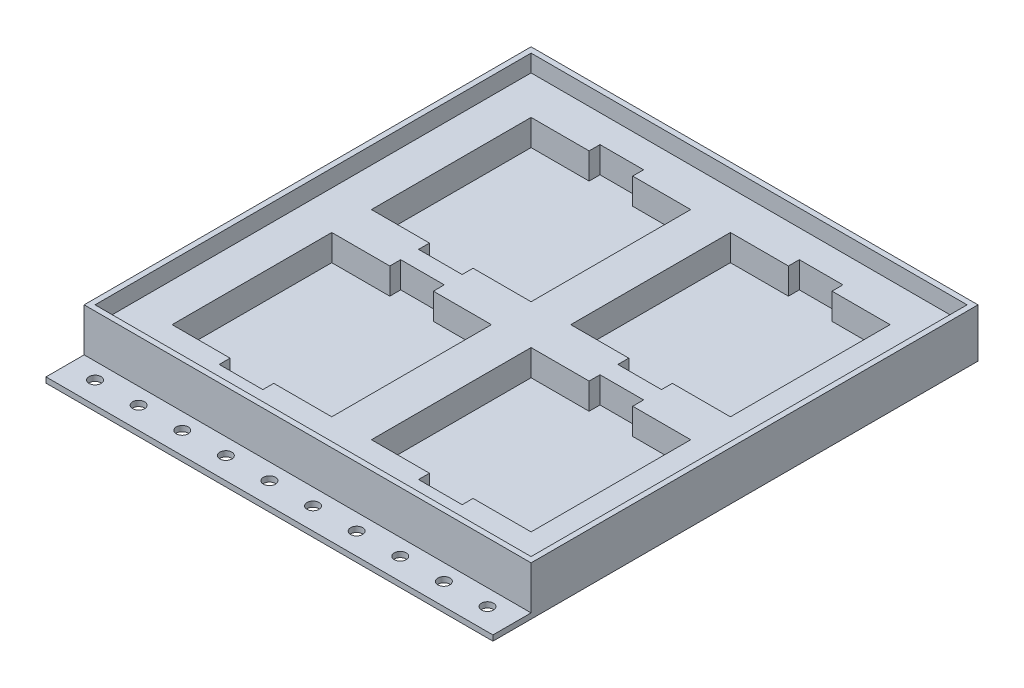
SolidWorks part; units mm, degrees
ref_plane "Front Plane" through (0, 0, 0) normal (0, 0, 1) x (1, 0, 0)
ref_plane "Top Plane" through (0, 0, 0) normal (0, 1, 0) x (1, 0, 0)
ref_plane "Right Plane" through (0, 0, 0) normal (1, 0, 0) x (0, 0, -1)
sketch "Sketch1" plane through (0, 0, 0) normal (0, 1, 0) x (1, 0, 0)
  line L1 (-152.4, -152.4) -> (152.4, -152.4)
  line L2 (-152.4, -152.4) -> (-152.4, 152.4)
  line L3 (-152.4, 152.4) -> (152.4, 152.4)
  line L4 (152.4, -152.4) -> (152.4, 152.4)
  line L5 (104.557, 11.557) -> (11.557, 11.557)
  line L6 (104.557, 11.557) -> (104.557, 104.557)
  line L7 (-11.557, 104.557) -> (-104.557, 104.557)
  line L8 (-11.557, 104.557) -> (-11.557, 11.557)
  line L9 (-11.557, 11.557) -> (-104.557, 11.557)
  line L10 (-104.557, 104.557) -> (-104.557, 11.557)
  line L11 (-11.557, 104.557) -> (-104.557, 11.557) construction
  line L12 (-11.557, 11.557) -> (-104.557, 104.557) construction
  line L13 (104.557, 104.557) -> (11.557, 104.557)
  line L14 (11.557, 11.557) -> (11.557, 104.557)
  line L15 (104.557, 11.557) -> (11.557, 104.557) construction
  line L16 (104.557, 104.557) -> (11.557, 11.557) construction
  line L17 (-104.557, -11.557) -> (-11.557, -11.557)
  line L18 (-104.557, -11.557) -> (-104.557, -104.557)
  line L19 (-104.557, -104.557) -> (-11.557, -104.557)
  line L20 (-11.557, -11.557) -> (-11.557, -104.557)
  line L21 (-104.557, -11.557) -> (-11.557, -104.557) construction
  line L22 (-104.557, -104.557) -> (-11.557, -11.557) construction
  line L23 (11.557, -11.557) -> (104.557, -11.557)
  line L24 (11.557, -11.557) -> (11.557, -104.557)
  line L25 (11.557, -104.557) -> (104.557, -104.557)
  line L26 (104.557, -11.557) -> (104.557, -104.557)
  line L27 (11.557, -11.557) -> (104.557, -104.557) construction
  line L28 (11.557, -104.557) -> (104.557, -11.557) construction
  point P0 (0, 0)
  point P6 (-58.057, 58.057)
  point P11 (58.057, 58.057)
  point P14 (0, 152.4)
  point P16 (-152.4, 0)
  point P18 (-58.057, -58.057)
  point P23 (58.057, -58.057)
  dimension "D1" = 93
  dimension "D2" = 304.8
  dimension "D3" = 23.114
  dimension "D4" = 23.114
extrude "Boss-Extrude1" add sketch "Sketch1" along normal blind 15.24
sketch "Sketch2" plane through (0, 0, 0) normal (0, -1, 0) x (-1, 0, 0)
  line L1 (152.4, -152.4) -> (-152.4, -152.4)
  line L2 (152.4, -152.4) -> (152.4, 152.4)
  line L3 (152.4, 152.4) -> (-152.4, 152.4)
  line L4 (-152.4, -152.4) -> (-152.4, 152.4)
extrude "Boss-Extrude2" add sketch "Sketch2" along normal blind 3.175
sketch "Sketch3" plane through (0, 15.24, 0) normal (0, 1, 0) x (1, 0, 0)
  line L1 (-152.4, -152.4) -> (152.4, -152.4)
  line L2 (-152.4, -152.4) -> (-152.4, 152.4)
  line L3 (-152.4, 152.4) -> (152.4, 152.4)
  line L4 (152.4, -152.4) -> (152.4, 152.4)
  line L5 (-127, -127) -> (127, -127)
  line L6 (-127, -127) -> (-127, 127)
  line L7 (-127, 127) -> (127, 127)
  line L8 (127, -127) -> (127, 127)
  point P10 (-127, 0)
  point P11 (0, 127)
  dimension "D1" = 254
  dimension "D2" = 254
extrude "Boss-Extrude3" add sketch "Sketch3" along normal blind 10
sketch "Sketch4" plane through (0, 25.24, 0) normal (0, 1, 0) x (1, 0, 0)
  line L0 (127, 127) -> (-127, 127) construction
  line L1 (-130.175, 130.175) -> (130.175, 130.175)
  line L2 (-130.175, 130.175) -> (-130.175, -130.175)
  line L3 (-130.175, -130.175) -> (130.175, -130.175)
  line L4 (130.175, 130.175) -> (130.175, -130.175)
  line L5 (-127, 127) -> (-127, -127) construction
  line L6 (127, -127) -> (127, 127) construction
  line L7 (-127, -127) -> (127, -127) construction
  dimension "D1" = 3.175
  dimension "D2" = 3.175
  dimension "D3" = 3.175
  dimension "D4" = 3.175
extrude "Cut-Extrude1" cut sketch "Sketch4" against normal offset from surface (25.24 mm away) 3.175 flip side to cut up to face at (0, -3.175, 0)
sketch "Sketch5" plane through (0, 0, 0) normal (0, 1, 0) x (1, 0, 0)
  line L0 (152.4, -152.4) -> (-152.4, -152.4) construction
  line L1 (-152.4, -152.4) -> (-152.4, 152.4) construction
  circle A0 centre (-139.7, -139.7) radius 3.4925
  circle A1 centre (-114.3, -139.7) radius 3.4925
  circle A2 centre (-88.9, -139.7) radius 3.4925
  circle A3 centre (-63.5, -139.7) radius 3.4925
  circle A4 centre (-38.1, -139.7) radius 3.4925
  circle A5 centre (-12.7, -139.7) radius 3.4925
  circle A6 centre (12.7, -139.7) radius 3.4925
  circle A7 centre (38.1, -139.7) radius 3.4925
  circle A8 centre (63.5, -139.7) radius 3.4925
  circle A9 centre (88.9, -139.7) radius 3.4925
  circle A10 centre (114.3, -139.7) radius 3.4925
  circle A11 centre (139.7, -139.7) radius 3.4925
  circle A12 centre (-139.7, -114.3) radius 3.4925
  circle A13 centre (-139.7, -88.9) radius 3.4925
  circle A14 centre (-139.7, -63.5) radius 3.4925
  circle A15 centre (-139.7, -38.1) radius 3.4925
  circle A16 centre (-139.7, -12.7) radius 3.4925
  circle A17 centre (-139.7, 12.7) radius 3.4925
  circle A18 centre (-139.7, 38.1) radius 3.4925
  circle A19 centre (-139.7, 63.5) radius 3.4925
  circle A20 centre (-139.7, 88.9) radius 3.4925
  circle A21 centre (-139.7, 114.3) radius 3.4925
  circle A22 centre (-139.7, 139.7) radius 3.4925
  circle A23 centre (-114.3, 139.7) radius 3.4925
  circle A24 centre (-88.9, 139.7) radius 3.4925
  circle A25 centre (-63.5, 139.7) radius 3.4925
  circle A26 centre (-38.1, 139.7) radius 3.4925
  circle A27 centre (-12.7, 139.7) radius 3.4925
  circle A28 centre (12.7, 139.7) radius 3.4925
  circle A29 centre (38.1, 139.7) radius 3.4925
  circle A30 centre (63.5, 139.7) radius 3.4925
  circle A31 centre (88.9, 139.7) radius 3.4925
  circle A32 centre (114.3, 139.7) radius 3.4925
  circle A33 centre (139.7, 139.7) radius 3.4925
  circle A34 centre (139.7, 114.3) radius 3.4925
  circle A35 centre (139.7, 88.9) radius 3.4925
  circle A36 centre (139.7, 63.5) radius 3.4925
  circle A37 centre (139.7, 38.1) radius 3.4925
  circle A38 centre (139.7, 12.7) radius 3.4925
  circle A39 centre (139.7, -12.7) radius 3.4925
  circle A40 centre (139.7, -38.1) radius 3.4925
  circle A41 centre (139.7, -63.5) radius 3.4925
  circle A42 centre (139.7, -88.9) radius 3.4925
  circle A43 centre (139.7, -114.3) radius 3.4925
  dimension "D1" = 6.985
  dimension "D2" = 12.7
  dimension "D3" = 12.7
  dimension "D4" = 12
  dimension "D5" = 12
  dimension "D6" = 12
  dimension "D7" = 11
extrude "Cut-Extrude2" cut sketch "Sketch5" against normal through all
sketch "Sketch6" plane through (0, 15.24, 0) normal (0, 1, 0) x (1, 0, 0)
  line L0 (-11.557, 104.557) -> (-104.557, 104.557) construction
  line L1 (-70.757, 104.557) -> (-45.357, 104.557)
  line L2 (-70.757, 104.557) -> (-70.757, 110.907)
  line L3 (-70.757, 110.907) -> (-45.357, 110.907)
  line L4 (-45.357, 104.557) -> (-45.357, 110.907)
  line L5 (11.557, -104.557) -> (104.557, -104.557) construction
  line L6 (-11.557, -11.557) -> (-104.557, -11.557) construction
  line L7 (-70.757, -11.557) -> (-45.357, -11.557)
  line L8 (-70.757, -11.557) -> (-70.757, -5.207)
  line L9 (-70.757, -5.207) -> (-45.357, -5.207)
  line L10 (-104.557, 11.557) -> (-11.557, 11.557) construction
  line L11 (-70.757, 11.557) -> (-45.357, 11.557)
  line L12 (-70.757, 11.557) -> (-70.757, 5.207)
  line L13 (-70.757, 5.207) -> (-45.357, 5.207)
  line L14 (-45.357, 11.557) -> (-45.357, 5.207)
  line L15 (-45.357, -11.557) -> (-45.357, -5.207)
  line L16 (-104.557, -104.557) -> (-11.557, -104.557) construction
  line L17 (-70.757, -104.557) -> (-45.357, -104.557)
  line L18 (-70.757, -104.557) -> (-70.757, -110.907)
  line L19 (-70.757, -110.907) -> (-45.357, -110.907)
  line L20 (-45.357, -104.557) -> (-45.357, -110.907)
  line L21 (70.757, -104.557) -> (45.357, -104.557)
  line L22 (70.757, -104.557) -> (70.757, -110.907)
  line L23 (70.757, -110.907) -> (45.357, -110.907)
  line L24 (45.357, -104.557) -> (45.357, -110.907)
  line L25 (104.557, -11.557) -> (11.557, -11.557) construction
  line L26 (70.757, -11.557) -> (45.357, -11.557)
  line L27 (70.757, -11.557) -> (70.757, -5.207)
  line L28 (70.757, -5.207) -> (45.357, -5.207)
  line L29 (45.357, -11.557) -> (45.357, -5.207)
  line L30 (11.557, 11.557) -> (104.557, 11.557) construction
  line L31 (70.757, 11.557) -> (45.357, 11.557)
  line L32 (70.757, 11.557) -> (70.757, 5.207)
  line L33 (70.757, 5.207) -> (45.357, 5.207)
  line L34 (45.357, 11.557) -> (45.357, 5.207)
  line L35 (104.557, 104.557) -> (11.557, 104.557) construction
  line L36 (70.757, 104.557) -> (45.357, 104.557)
  line L37 (70.757, 104.557) -> (70.757, 110.907)
  line L38 (70.757, 110.907) -> (45.357, 110.907)
  line L39 (45.357, 104.557) -> (45.357, 110.907)
  point P25 (-70.757, 8.382)
  point P27 (-58.057, 11.557)
  point P28 (-58.057, 5.207)
  point P29 (-58.057, 104.557)
  point P30 (-58.057, 110.907)
  point P53 (70.757, -8.382)
  point P54 (45.357, -8.382)
  point P55 (58.057, -104.557)
  dimension "D1" = 25.4
  dimension "D2" = 6.35
  dimension "D3" = 6.35
extrude "Cut-Extrude3" cut sketch "Sketch6" against normal up to surface (15.24 mm away) up to face at (-58.057, 0, -58.057)
sketch "Sketch7" plane through (0, 0, -130.175) normal (0, 0, -1) x (-1, 0, 0)
  line L1 (167.8665, -118.5251) -> (-220.3422, -118.5251)
  line L2 (167.8665, -118.5251) -> (167.8665, 67.4439)
  line L3 (167.8665, 67.4439) -> (-220.3422, 67.4439)
  line L4 (-220.3422, -118.5251) -> (-220.3422, 67.4439)
extrude "Cut-Extrude4" cut sketch "Sketch7" along normal through all
sketch "Sketch8" plane through (-130.175, 0, 0) normal (-1, 0, 0) x (0, 0, 1)
  line L1 (-237.2877, -205.7244) -> (307.7637, -205.7244)
  line L2 (-237.2877, -205.7244) -> (-237.2877, 257.5416)
  line L3 (-237.2877, 257.5416) -> (307.7637, 257.5416)
  line L4 (307.7637, -205.7244) -> (307.7637, 257.5416)
extrude "Cut-Extrude5" cut sketch "Sketch8" along normal through all
sketch "Sketch9" plane through (130.175, 0, 0) normal (1, 0, 0) x (0, 0, -1)
  line L1 (-265.9255, 236.578) -> (319.6138, 236.578)
  line L2 (-265.9255, 236.578) -> (-265.9255, -147.0614)
  line L3 (-265.9255, -147.0614) -> (319.6138, -147.0614)
  line L4 (319.6138, 236.578) -> (319.6138, -147.0614)
extrude "Cut-Extrude6" cut sketch "Sketch9" along normal through all
